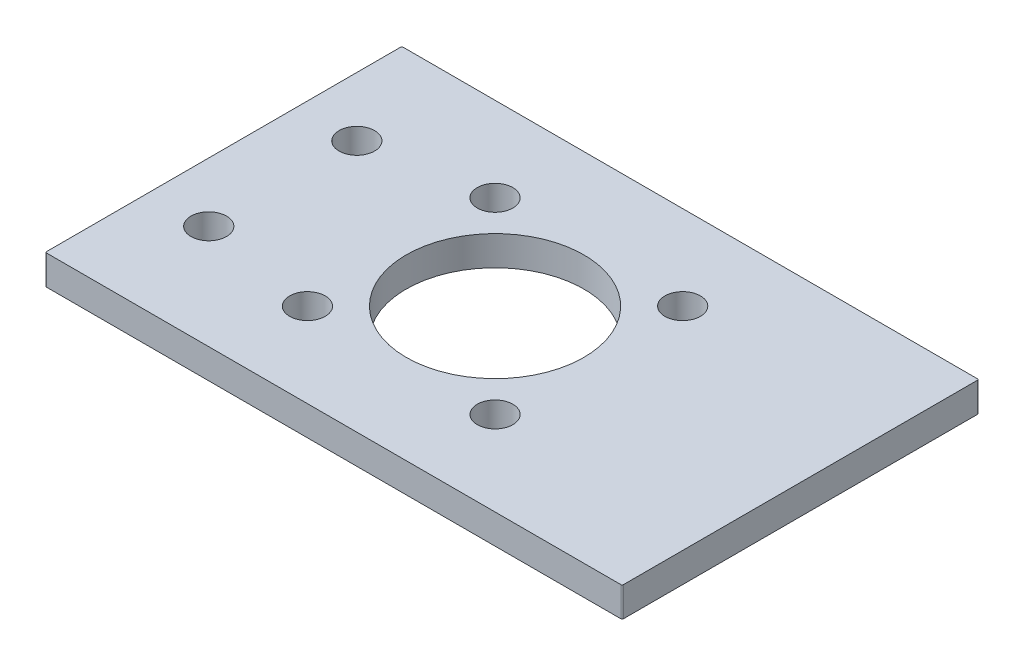
SolidWorks part; units mm, degrees
material "AISI 1020"
ref_plane "Front Plane" through (0, 0, 0) normal (0, 0, 1) x (1, 0, 0)
ref_plane "Top Plane" through (0, 0, 0) normal (0, 1, 0) x (1, 0, 0)
ref_plane "Right Plane" through (0, 0, 0) normal (1, 0, 0) x (0, 0, -1)
sketch "Sketch1" plane through (0, 0, 0) normal (0, 1, 0) x (1, 0, 0)
  line L0 (-61.849, 38.227) -> (61.849, -38.227) construction
  line L18 (61.849, -38.227) -> (-61.849, -38.227)
  line L24 (-61.849, -38.227) -> (-61.849, 38.227)
  line L25 (-61.849, 38.227) -> (61.849, 38.227)
  line L26 (61.849, 38.227) -> (61.849, -38.227)
  point P0 (0, 0)
  point P1 (0, 0)
  dimension "D1" = 76.454
  dimension "D2" = 123.698
extrude "Boss-Extrude1" add sketch "Sketch1" along normal blind 6.35
sketch "Sketch6" plane through (0, 6.35, 0) normal (0, 1, 0) x (1, 0, 0)
  line L0 (61.849, -38.227) -> (61.849, 38.227) construction
  line L1 (-61.849, 38.227) -> (-61.849, -38.227) construction
  line L2 (-49.149, -15.875) -> (-49.149, 15.875) construction
  circle A0 centre (-3.6332, 0) radius 19.05
  circle A4 centre (16.4825, 20.1158) radius 3.81
  circle A5 centre (-23.749, 20.1158) radius 3.81
  circle A6 centre (-23.749, -20.1158) radius 3.81
  circle A7 centre (16.4825, -20.1158) radius 3.81
  circle A8 centre (-49.149, 15.875) radius 3.81
  circle A9 centre (-49.149, -15.875) radius 3.81
  point P8 (61.849, 0)
  point P20 (-49.149, 0)
  point P21 (-61.849, 0)
  dimension "D3" = 38.1
  dimension "D4" = 40.2315
  dimension "D7" = 7.62
  dimension "D10" = 7.62
  dimension "D2" = 40.2315
  dimension "D5" = 20.1158
  dimension "D6" = 20.1158
  dimension "D8" = 31.75
  dimension "D9" = 12.7
  dimension "D11" = 25.4
extrude "Cut-Extrude5" cut sketch "Sketch6" against normal through all
fillet "Fillet1" radius 0.254 4 edges at (61.849, 3.175, -38.227) (61.849, 3.175, 38.227) (-61.849, 3.175, -38.227) (-61.849, 3.175, 38.227)
